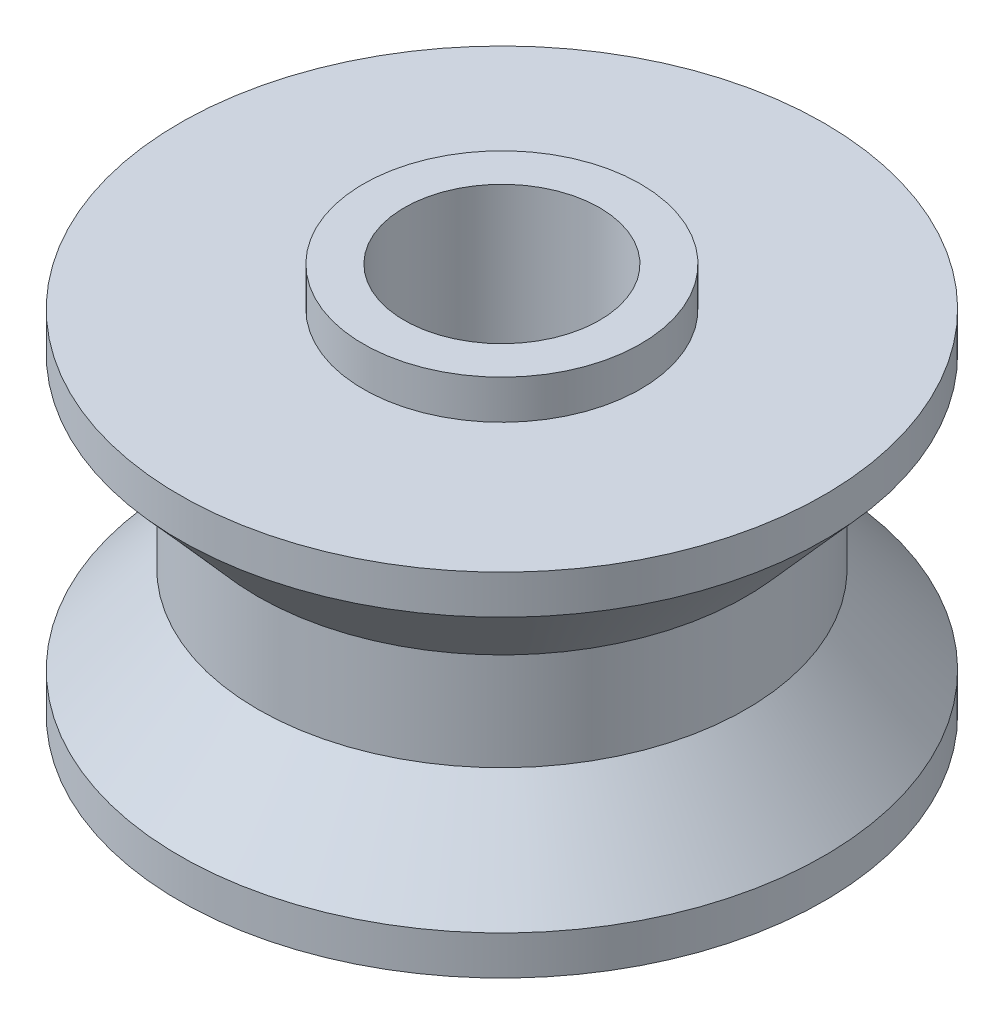
SolidWorks part; units mm, degrees
material "不锈钢 (铁素体)"
ref_plane "前视基准面" through (0, 0, 0) normal (0, 0, 1) x (1, 0, 0)
ref_plane "上视基准面" through (0, 0, 0) normal (0, 1, 0) x (1, 0, 0)
ref_plane "右视基准面" through (0, 0, 0) normal (1, 0, 0) x (0, 0, -1)
sketch "草图1" plane through (0, 0, 0) normal (0, 0, 1) x (1, 0, 0)
  line L0 (2.5, 5.5) -> (3.55, 5.5)
  line L1 (3.55, 5.5) -> (3.55, 4.5)
  line L2 (3.55, 4.5) -> (8.25, 4.5)
  line L3 (8.25, 4.5) -> (8.25, 3.5)
  line L4 (8.25, 3.5) -> (6.25, 1.25)
  line L5 (6.25, 1.25) -> (6.25, -1.25)
  line L6 (0, 0) -> (6.25, 0) construction
  line L7 (2.5, 5.5) -> (2.5, -5.5)
  line L8 (0, 0) -> (0, 4.5455) construction
  line L9 (8.25, -3.5) -> (6.25, -1.25)
  line L10 (8.25, -4.5) -> (8.25, -3.5)
  line L11 (3.55, -4.5) -> (8.25, -4.5)
  line L12 (3.55, -5.5) -> (3.55, -4.5)
  line L13 (2.5, -5.5) -> (3.55, -5.5)
  point P17 (2.5, -8.9745)
  dimension "D1" = 2.5
  dimension "D2" = 5
  dimension "D3" = 7
  dimension "D4" = 9
  dimension "D5" = 11
  dimension "D6" = 7.1
  dimension "D7" = 12.5
  dimension "D8" = 16.5
revolve "旋转1" add sketch "草图1" angle 360 about L8
